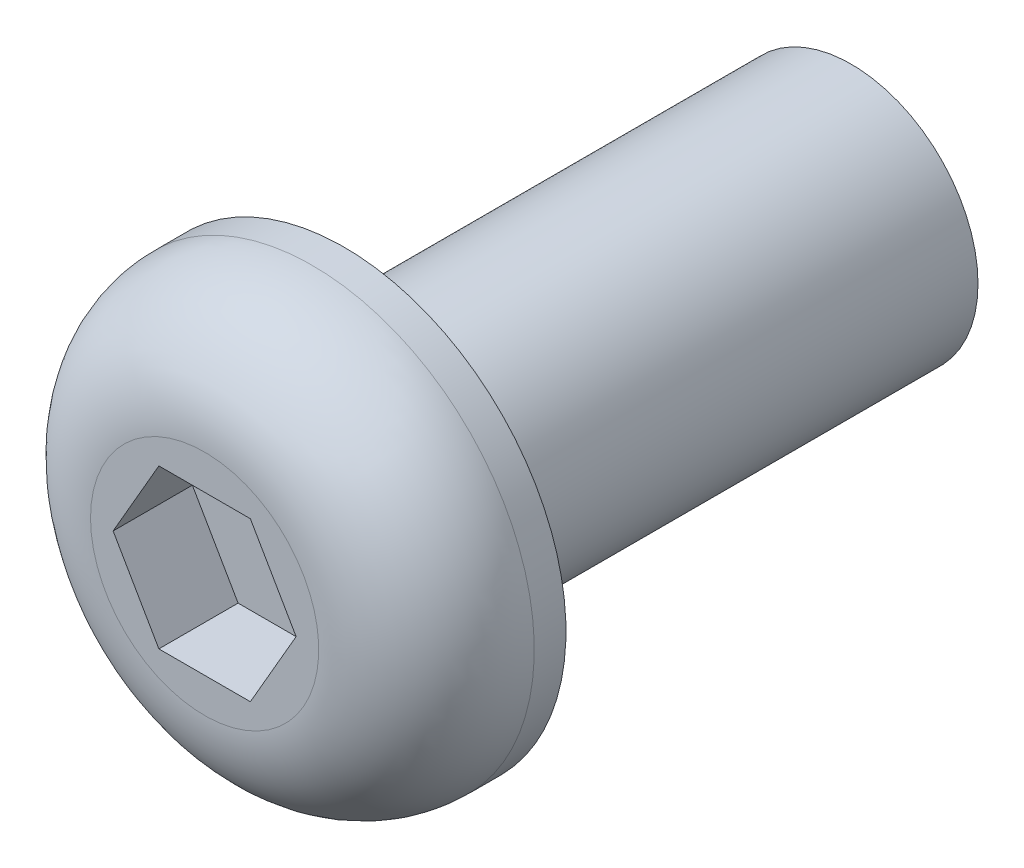
SolidWorks part; units mm, degrees
material "AISI 304"
ref_plane "Front Plane" through (0, 0, 0) normal (0, 0, 1) x (1, 0, 0)
ref_plane "Top Plane" through (0, 0, 0) normal (0, 1, 0) x (1, 0, 0)
ref_plane "Right Plane" through (0, 0, 0) normal (1, 0, 0) x (0, 0, -1)
sketch "Sketch1" plane through (0, 0, 0) normal (0, 0, 1) x (1, 0, 0)
  circle A0 centre (0, 0) radius 4
  dimension "D1" = 8
extrude "Extrude1" add sketch "Sketch1" against normal blind 16
sketch "Sketch2" plane through (0, 0, 0) normal (1, 0, 0) x (0, 0, -1)
  line L0 (0, 0) -> (-10.9859, 0) construction
  line L1 (0, 0) -> (0, 7)
  line L2 (0, 7) -> (-1, 7)
  line L3 (-4.4, 0) -> (-4.4, 3.6)
  line L4 (0, 0) -> (-4.4, 0)
  arc A0 (-4.4, 3.6) -> (-1, 7) centre (-1, 3.6) cw
  dimension "D1" = 4.4
  dimension "D2" = 14
  dimension "D3" = 1
revolve "Revolve1" add sketch "Sketch2" angle 360 about L0
sketch "Sketch3" plane through (0, 0, 4.4) normal (0, 0, 1) x (1, 0, 0)
  line L1 (-1.4434, 2.5) -> (-2.8868, 0)
  line L2 (-2.8868, 0) -> (-1.4434, -2.5)
  line L3 (-1.4434, -2.5) -> (1.4434, -2.5)
  line L4 (1.4434, -2.5) -> (2.8868, 0)
  line L5 (2.8868, 0) -> (1.4434, 2.5)
  line L6 (1.4434, 2.5) -> (-1.4434, 2.5)
  circle A0 centre (0, 0) radius 2.5 construction
  dimension "D1" = 5
extrude "Cut-Extrude1" cut sketch "Sketch3" against normal blind 2.5
